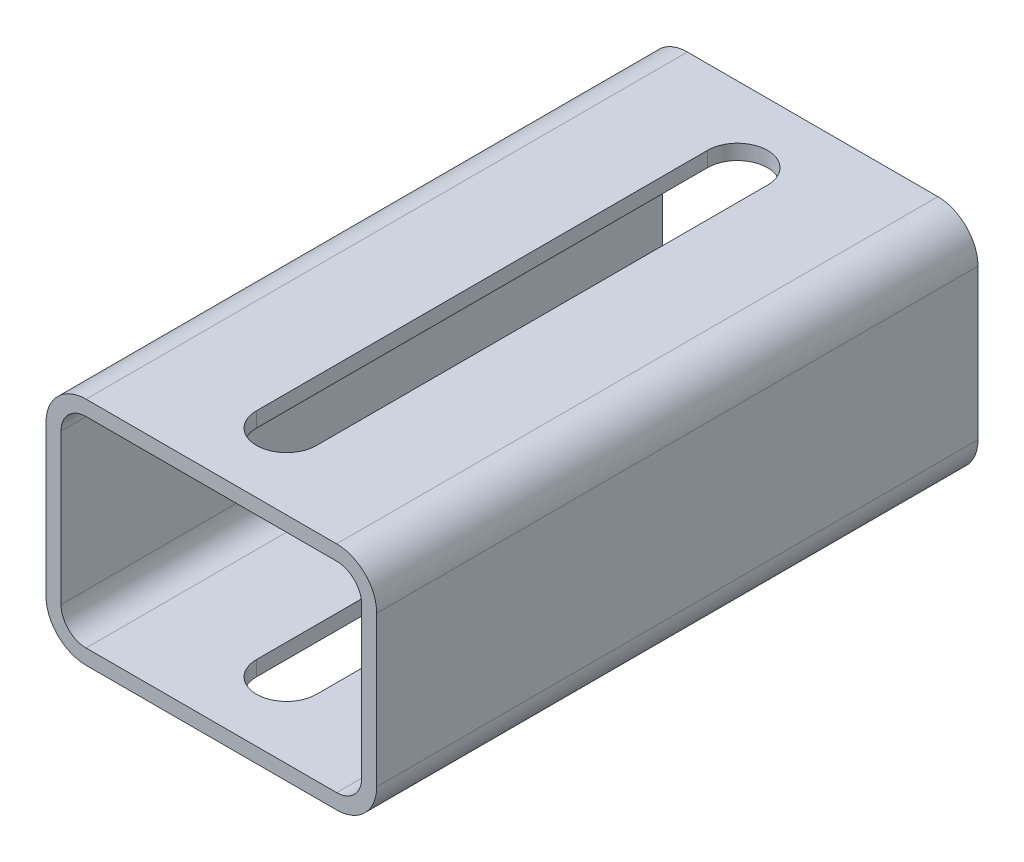
SolidWorks part; units mm, degrees
ref_plane "Front Plane" through (0, 0, 0) normal (0, 0, 1) x (1, 0, 0)
ref_plane "Top Plane" through (0, 0, 0) normal (0, 1, 0) x (1, 0, 0)
ref_plane "Right Plane" through (0, 0, 0) normal (1, 0, 0) x (0, 0, -1)
sketch "Sketch1" plane through (0, 0, 0) normal (0, 0, 1) x (1, 0, 0)
  line L1 (-25, -20) -> (25, -20)
  line L2 (-30, -15) -> (-30, 15)
  line L3 (-25, 20) -> (25, 20)
  line L4 (30, -15) -> (30, 15)
  line L5 (-30, -20) -> (30, 20) construction
  line L6 (-30, 20) -> (30, -20) construction
  arc A0 (25, 20) -> (30, 15) centre (25, 15) cw
  arc A1 (25, -20) -> (30, -15) centre (25, -15) ccw
  arc A2 (-25, -20) -> (-30, -15) centre (-25, -15) cw
  arc A3 (-30, 15) -> (-25, 20) centre (-25, 15) cw
  point P0 (0, 0)
  dimension "D3" = 5
  dimension "D1" = 60
  dimension "D2" = 40
extrude "Extrude-Thin1" add sketch "Sketch1" along normal mid plane 120 thin
sketch "Sketch3" plane through (0, 23, 0) normal (0, 1, 0) x (1, 0, 0)
  line L0 (0, 45) -> (0, -45) construction
  line L3 (6, 45) -> (6, -45)
  line L4 (-6, 45) -> (-6, -45)
  arc A2 (6, 45) -> (-6, 45) centre (0, 45) ccw
  arc A3 (-6, -45) -> (6, -45) centre (0, -45) ccw
  point P3 (0, 0)
  point P8 (0, 0)
  dimension "D2" = 6
  dimension "D1" = 90
extrude "Cut-Extrude1" cut sketch "Sketch3" against normal through all
